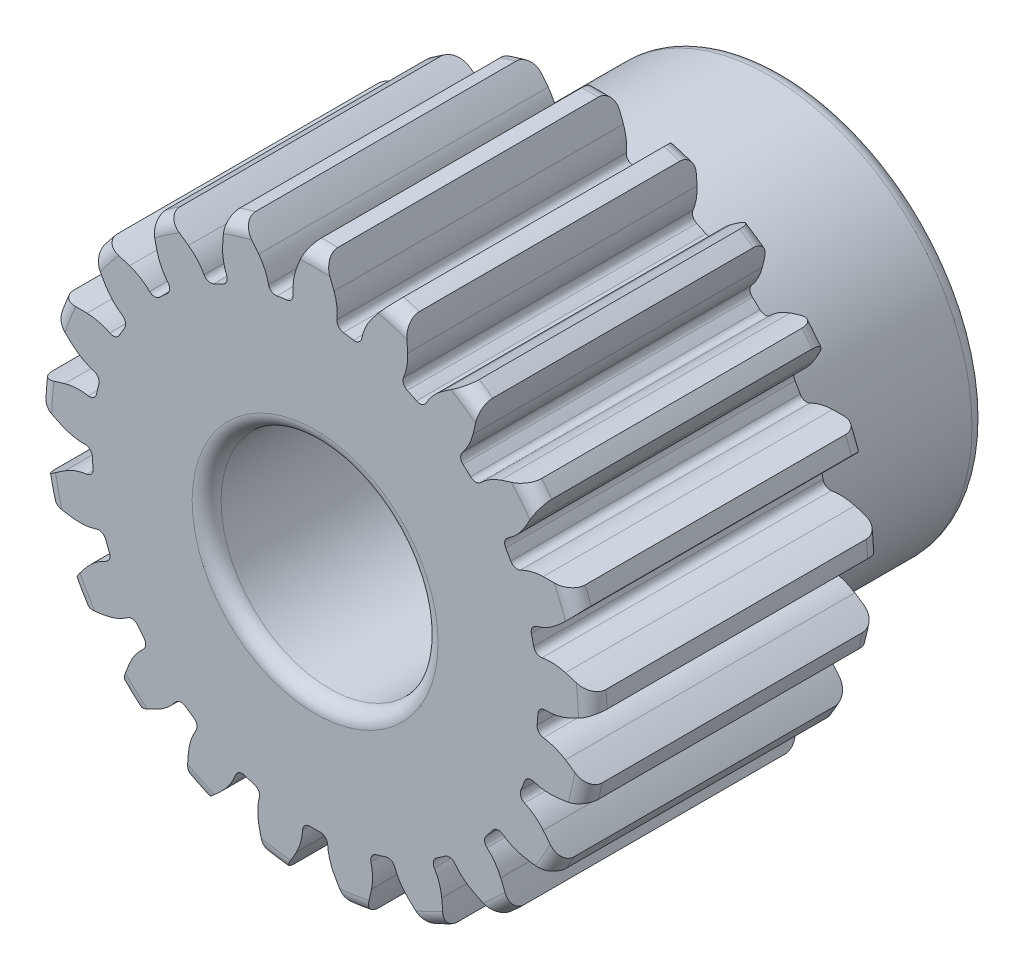
SolidWorks part; units mm, degrees
ref_plane "Front Plane" through (0, 0, 0) normal (0, 0, 1) x (1, 0, 0)
ref_plane "Top Plane" through (0, 0, 0) normal (0, 1, 0) x (1, 0, 0)
ref_plane "Right Plane" through (0, 0, 0) normal (1, 0, 0) x (0, 0, -1)
sketch "Sketch1" plane through (0, 0, 0) normal (0, 0, 1) x (1, 0, 0)
  line L0 (6.3727, 23.552) -> (8.0019, 23.0494)
  line L1 (-24.384, 0) -> (24.384, 0) construction
  line L2 (0, 24.384) -> (0, 22.225) construction
  line L3 (0, 22.225) -> (0, 19.5792) construction
  line L4 (-0.8524, 24.384) -> (0.8524, 24.384)
  line L5 (-0.8524, 24.384) -> (-2.6677, 19.3966)
  line L6 (0.8524, 24.384) -> (2.6677, 19.3966)
  line L7 (6.3727, 23.552) -> (3.168, 19.3212)
  line L8 (-3.3249, -24.384) -> (3.3249, -24.384) construction
  line L9 (3.3249, -24.384) -> (0, -30.1428) construction
  line L10 (0, -30.1428) -> (-3.3249, -24.384) construction
  line L11 (0, -30.1428) -> (0, -29.9137) construction
  line L12 (-0.1323, -29.9137) -> (0.1323, -29.9137) construction
  line L13 (0, -24.6131) -> (0, -24.384) construction
  line L14 (7.1873, 23.3007) -> (0, 0) construction
  line L15 (3.1926, -24.6131) -> (-3.1926, -24.6131) construction
  line L16 (8.0019, 23.0494) -> (8.2664, 17.7485)
  line L17 (-3.2587, -24.4986) -> (3.2587, -24.4986) construction
  line L18 (0, 0) -> (-1.9224, 20.1125) construction
  line L19 (0, 0) -> (4.0912, 19.7856) construction
  circle A0 centre (0, 0) radius 24.384
  circle A1 centre (0, 0) radius 22.225 construction
  circle A2 centre (0, 0) radius 9.525
  circle A3 centre (0, 0) radius 19.5792
  arc A4 (-1.6609, 22.1629) -> (1.6609, 22.1629) centre (0, 0) cw
  circle A5 centre (0, 0) radius 17.78 construction
  arc A6 (-2.4743, 19.4222) -> (-1.9224, 20.1125) centre (-2.5546, 20.0521) ccw
  circle A8 centre (0, 0) radius 20.1083 construction
  arc A10 (-1.6609, 22.1629) -> (-1.9224, 20.1125) centre (2.7463, 20.5588) ccw
  arc A11 (-0.716, 24.384) -> (-1.6609, 22.1629) centre (19.6817, 14.3948) ccw
  arc A13 (3.3604, 19.2886) -> (4.0912, 19.7856) centre (3.4694, 19.9142) ccw
  arc A15 (4.9455, 21.6678) -> (4.0912, 19.7856) centre (8.6841, 18.8359) ccw
  arc A16 (6.5032, 23.5117) -> (4.9455, 21.6678) centre (23.0502, 7.954) ccw
  arc A17 (2.4743, 19.4222) -> (1.9224, 20.1125) centre (2.5546, 20.0521) cw
  arc A18 (1.6609, 22.1629) -> (1.9224, 20.1125) centre (-2.7463, 20.5588) cw
  arc A19 (0.716, 24.384) -> (1.6609, 22.1629) centre (-19.6817, 14.3948) cw
  arc A20 (8.0892, 17.83) -> (7.7653, 18.6523) centre (8.3515, 18.4083) cw
  arc A21 (8.1197, 20.6887) -> (7.7653, 18.6523) centre (3.4355, 20.4549) cw
  arc A22 (7.8715, 23.0897) -> (8.1197, 20.6887) centre (-14.5644, 19.5566) cw
  point P5 (0, 24.384)
  point P8 (7.1873, 23.3007)
  point P9 (13.736, 20.147)
  point P10 (19.0642, 15.2032)
  point P11 (22.6984, 8.9085)
  point P12 (24.3158, 1.8222)
  point P13 (23.7726, -5.426)
  point P14 (21.1172, -12.192)
  point P15 (16.5853, -17.8747)
  point P16 (10.5798, -21.9692)
  point P17 (3.6342, -24.1117)
  point P18 (-3.6342, -24.1117)
  point P19 (-10.5798, -21.9692)
  point P20 (-16.5853, -17.8747)
  point P21 (-21.1172, -12.192)
  point P22 (0, 0)
  point P37 (-3.3249, -24.384)
  point P47 (0, -24.4986)
  point P48 (-23.7726, -5.426)
  point P49 (3.3249, -24.384)
  point P53 (9.9746, -24.384)
  point P54 (16.6243, -24.384)
  point P55 (23.274, -24.384)
  point P56 (29.9237, -24.384)
  point P57 (36.5735, -24.384)
  point P58 (43.2232, -24.384)
  point P59 (49.8729, -24.384)
  point P60 (56.5226, -24.384)
  point P61 (63.1723, -24.384)
  point P62 (69.8221, -24.384)
  point P63 (-24.3158, 1.8222)
  point P64 (-22.6984, 8.9085)
  point P65 (-19.0642, 15.2032)
  point P66 (-13.736, 20.147)
  point P69 (-7.1873, 23.3007)
  point P81 (0, 17.78)
  dimension "OD" = 48.768
  dimension "Shaft Diameter" = 19.05
  dimension "Pitch Diameter" = 44.45
  dimension "Hub Diameter" = 35.56
  dimension "D4" = 0.635
  dimension "Driven Dim* Addendum (a)" = 2.159
  dimension "Dedendum (b)" = 2.6458
  dimension "D2" = 6.6497
  dimension "D3" = 0.2646
  dimension "Pressure Angle" = 20
  dimension "Clearance" = 0.5292
  dimension "D5" = 17.143
  dimension "D1" = 3.3249
  dimension "Gear Pitch" = 12
  dimension "Teeth" = 21
sketch "Sketch2" plane through (0, 0, 0) normal (1, 0, 0) x (0, 0, -1)
  line L0 (-20.574, 23.114) -> (-20.574, -23.114)
  line L1 (-19.304, -24.384) -> (3.556, -24.384)
  line L2 (4.826, -23.114) -> (4.826, -19.05)
  line L3 (6.096, -17.78) -> (19.304, -17.78)
  line L4 (20.574, -16.51) -> (20.574, 16.51)
  line L5 (19.304, 17.78) -> (6.096, 17.78)
  line L6 (4.826, 19.05) -> (4.826, 23.114)
  line L7 (3.556, 24.384) -> (-19.304, 24.384)
  line L8 (20.574, 0) -> (-20.574, 0) construction
  line L10 (4.826, 17.78) -> (-20.574, 17.78) construction
  line L13 (20.574, 9.525) -> (0, 9.525) construction
  line L15 (-20.574, 9.525) -> (0, 9.525) construction
  line L17 (20.574, -9.525) -> (0, -9.525) construction
  line L18 (0, -9.525) -> (-20.574, -9.525) construction
  arc A0 (-20.574, -23.114) -> (-19.304, -24.384) centre (-19.304, -23.114) ccw
  arc A1 (3.556, -24.384) -> (4.826, -23.114) centre (3.556, -23.114) ccw
  arc A2 (4.826, -19.05) -> (6.096, -17.78) centre (6.096, -19.05) cw
  arc A3 (20.574, -16.51) -> (19.304, -17.78) centre (19.304, -16.51) cw
  arc A4 (4.826, 19.05) -> (6.096, 17.78) centre (6.096, 19.05) ccw
  arc A5 (-20.574, 23.114) -> (-19.304, 24.384) centre (-19.304, 23.114) cw
  arc A6 (3.556, 24.384) -> (4.826, 23.114) centre (3.556, 23.114) cw
  arc A7 (19.304, 17.78) -> (20.574, 16.51) centre (19.304, 16.51) cw
  point P40 (20.574, 17.78)
  dimension "Radius" = 1.27
  dimension "Hub Width" = 15.748
  dimension "Overall Width" = 41.148
sketch "Sketch3" plane through (0, 0, 0) normal (1, 0, 0) x (0, 0, -1)
  line L0 (19.304, 9.525) -> (-19.304, 9.525)
  line L1 (20.574, -16.51) -> (20.574, 16.51) construction
  line L2 (19.304, 17.78) -> (6.096, 17.78) construction
  line L3 (4.826, 19.05) -> (4.826, 23.114) construction
  line L4 (3.556, 24.384) -> (-19.304, 24.384) construction
  line L5 (-20.574, 23.114) -> (-20.574, -23.114) construction
  line L6 (20.574, 10.795) -> (20.574, 16.51)
  line L7 (19.304, 17.78) -> (6.096, 17.78)
  line L8 (4.826, 19.05) -> (4.826, 23.114)
  line L9 (3.556, 24.384) -> (-19.304, 24.384)
  line L10 (-20.574, 23.114) -> (-20.574, 10.795)
  line L11 (20.574, 9.525) -> (0, 9.525) construction
  arc A8 (20.574, 16.51) -> (19.304, 17.78) centre (19.304, 16.51) ccw construction
  arc A9 (4.826, 19.05) -> (6.096, 17.78) centre (6.096, 19.05) ccw construction
  arc A10 (4.826, 23.114) -> (3.556, 24.384) centre (3.556, 23.114) ccw construction
  arc A11 (-19.304, 24.384) -> (-20.574, 23.114) centre (-19.304, 23.114) ccw construction
  arc A12 (20.574, 16.51) -> (19.304, 17.78) centre (19.304, 16.51) ccw
  arc A13 (4.826, 19.05) -> (6.096, 17.78) centre (6.096, 19.05) ccw
  arc A14 (4.826, 23.114) -> (3.556, 24.384) centre (3.556, 23.114) ccw
  arc A15 (-19.304, 24.384) -> (-20.574, 23.114) centre (-19.304, 23.114) ccw
  arc A16 (-20.574, 10.795) -> (-19.304, 9.525) centre (-19.304, 10.795) ccw
  arc A17 (19.304, 9.525) -> (20.574, 10.795) centre (19.304, 10.795) ccw
revolve "Revolve1" add sketch "Sketch3" angle 360 about L8
sketch "Sketch4" plane through (0, 0, 20.574) normal (0, 0, 1) x (1, 0, 0)
  circle A9 centre (0, 0) radius 24.384 construction
  circle A21 centre (0, 0) radius 19.5792 construction
  arc A22 (3.3604, 19.2886) -> (4.0912, 19.7856) centre (3.4694, 19.9142) ccw construction
  arc A23 (4.9455, 21.6678) -> (4.0912, 19.7856) centre (8.6841, 18.8359) ccw construction
  arc A24 (6.5032, 23.5117) -> (4.9455, 21.6678) centre (23.0502, 7.954) ccw construction
  arc A25 (1.6609, 22.1629) -> (0.716, 24.384) centre (-19.6817, 14.3948) ccw construction
  arc A26 (1.9224, 20.1125) -> (1.6609, 22.1629) centre (-2.7463, 20.5588) ccw construction
  arc A27 (1.9224, 20.1125) -> (2.4743, 19.4222) centre (2.5546, 20.0521) ccw construction
  arc A28 (6.495, 23.5031) -> (0.7212, 24.3733) centre (0, 0) ccw
  arc A29 (3.3604, 19.2886) -> (2.4743, 19.4222) centre (0, 0) ccw
  arc A30 (3.3604, 19.2886) -> (4.0912, 19.7856) centre (3.4694, 19.9142) ccw
  arc A31 (4.9455, 21.6678) -> (4.0912, 19.7856) centre (8.6841, 18.8359) ccw
  arc A32 (6.495, 23.5031) -> (4.9455, 21.6678) centre (23.0502, 7.954) ccw
  arc A33 (1.6609, 22.1629) -> (0.7212, 24.3733) centre (-19.6817, 14.3948) ccw
  arc A34 (1.9224, 20.1125) -> (1.6609, 22.1629) centre (-2.7463, 20.5588) ccw
  arc A35 (1.9224, 20.1125) -> (2.4743, 19.4222) centre (2.5546, 20.0521) ccw
extrude "Cut-Extrude1" cut sketch "Sketch4" against normal through all both and the other way through all
pattern_circular "CirPattern1" count 21 every 17.143 about axis through (0, 0, 0) along (0, 0, 1) of "Cut-Extrude1"
equation "\"D3@Sketch1\"=(1/\"Gear Pitch@Sketch1\")/8"
equation "\"D2@Sketch1\"=3.1416/\"Gear Pitch@Sketch1\""
equation "\"Dedendum (b)@Sketch1\"=1.25/\"Gear Pitch@Sketch1\""
equation "\"D1@Sketch1\"=1.5708/\"Gear Pitch@Sketch1\""
equation "\"D4@Sketch1\"=.3/\"Gear Pitch@Sketch1\""
equation "\"Clearance@Sketch1\" = .25 / \"Gear Pitch@Sketch1\""
equation "\"D1@CirPattern1\"=\"Teeth@Sketch1\""
equation "\"D5@Sketch1\"=360/\"Teeth@Sketch1\""
equation "\"D2@CirPattern1\"=\"D5@Sketch1\""
equation "\"Radius@Sketch2\"=.6/\"Gear Pitch@Sketch1\""
